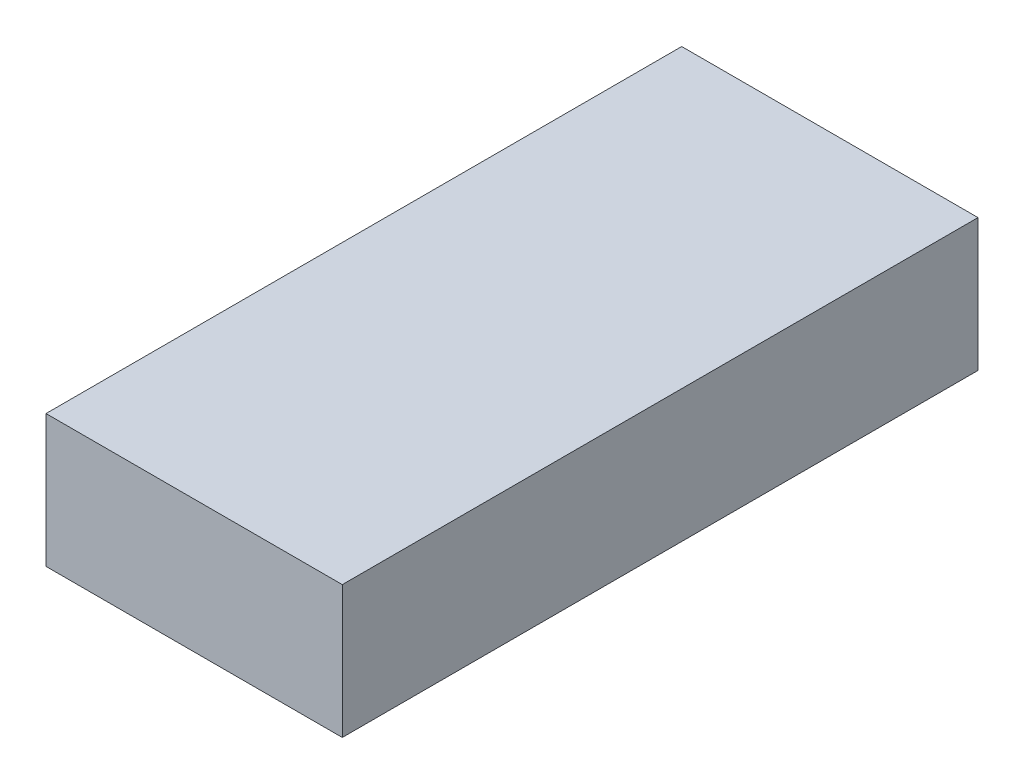
SolidWorks part; units mm, degrees
ref_plane "Front Plane" through (0, 0, 0) normal (1, 0, 0) x (0, 1, 0)
ref_plane "Top Plane" through (0, 0, 0) normal (0, 0, 1) x (0, 1, 0)
ref_plane "Right Plane" through (0, 0, 0) normal (0, 1, 0) x (-1, 0, 0)
sketch "Sketch1" plane through (0, 0, 0) normal (0, 0, 1) x (0, 1, 0)
  line L1 (-8.3312, -18.6436) -> (8.3312, -18.6436)
  line L2 (-8.3312, -18.6436) -> (-8.3312, 18.6436)
  line L3 (-8.3312, 18.6436) -> (8.3312, 18.6436)
  line L4 (8.3312, -18.6436) -> (8.3312, 18.6436)
  line L5 (-8.3312, -18.6436) -> (8.3312, 18.6436) construction
  line L6 (-8.3312, 18.6436) -> (8.3312, -18.6436) construction
  point P0 (0, 0)
  dimension "D1" = 16.6624
  dimension "D2" = 37.2872
extrude "Boss-Extrude1" add sketch "Sketch1" along normal mid plane 80
